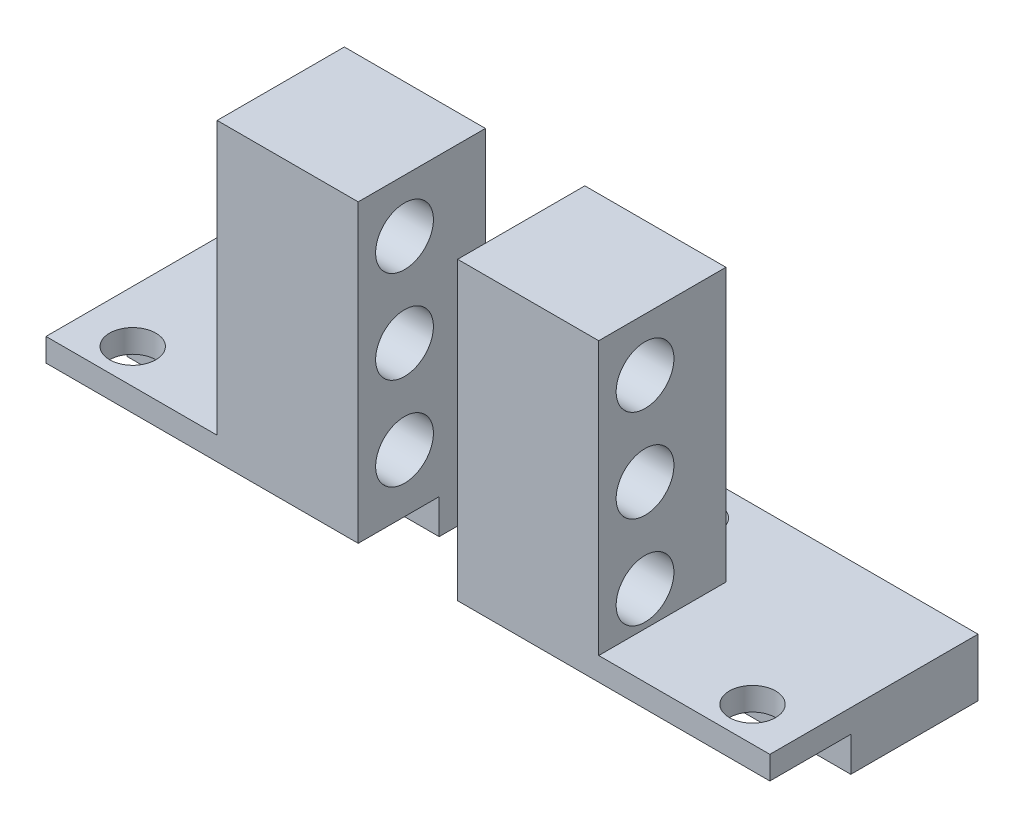
SolidWorks part; units mm, degrees
ref_plane "Front Plane" through (0, 0, 0) normal (0, 0, 1) x (1, 0, 0)
ref_plane "Top Plane" through (0, 0, 0) normal (0, 1, 0) x (1, 0, 0)
ref_plane "Right Plane" through (0, 0, 0) normal (1, 0, 0) x (0, 0, -1)
sketch "Sketch1" plane through (0, 0, 0) normal (0, 0, 1) x (1, 0, 0)
  line L0 (0, 0) -> (12.2, 0)
  line L1 (12.2, 0) -> (12.2, -28.578)
  line L2 (12.2, -28.578) -> (-14.8, -28.578)
  line L3 (-14.8, -28.578) -> (-14.8, -23.578)
  line L4 (-14.8, -23.578) -> (0, -23.578)
  line L5 (0, -23.578) -> (0, 0)
  dimension "D1" = 27
  dimension "D2" = 28.578
  dimension "D3" = 12.2
  dimension "D4" = 5
extrude "Boss-Extrude1" add sketch "Sketch1" against normal blind 18
sketch "Sketch2" plane through (0, 0, 0) normal (-1, 0, 0) x (0, 0, 1)
  line L1 (-18, -23.578) -> (-11, -23.578)
  line L2 (-18, -23.578) -> (-18, 0)
  line L3 (-18, 0) -> (-11, 0)
  line L4 (-11, -23.578) -> (-11, 0)
  line L5 (-18, -23.578) -> (0, -23.578) construction
  line L8 (0, -28.578) -> (-7, -28.578)
  line L9 (0, -28.578) -> (0, -25.578)
  line L10 (0, -25.578) -> (-7, -25.578)
  line L11 (-7, -28.578) -> (-7, -25.578)
  circle A0 centre (-4.0049, -20.578) radius 2.5
  circle A1 centre (-4.0049, -12.578) radius 2.5
  circle A2 centre (-4.0049, -4.578) radius 2.5
  dimension "D2" = 5
  dimension "D1" = 7
  dimension "D3" = 3
  dimension "D4" = 8
  dimension "D5" = 8
  dimension "D6" = 3
  dimension "D7" = 7
extrude "Cut-Extrude1" cut sketch "Sketch2" against normal through all and the other way through all
sketch "Sketch3" plane through (0, -23.578, 0) normal (0, 1, 0) x (1, 0, 0)
  line L0 (12.2, 18) -> (12.2, 11) construction
  line L1 (12.2, 18) -> (12.2, 11) construction
  line L2 (0, 11) -> (0, 0) construction
  line L3 (0, 11) -> (0, 0) construction
  line L4 (12.2, 11) -> (0, 11) construction
  line L5 (12.2, 11) -> (0, 11) construction
  line L6 (-14.8, 18) -> (-14.8, 0) construction
  line L7 (0, 0) -> (-14.8, 0) construction
  circle A0 centre (-10.3, 3) radius 2
  circle A1 centre (6.1, 14.5) radius 2
  point P10 (6.1, 11)
  point P11 (12.2, 14.5)
  dimension "D1" = 4
  dimension "D2" = 4
  dimension "D3" = 4.5
  dimension "D4" = 3
extrude "Cut-Extrude2" cut sketch "Sketch3" against normal through all
ref_plane "Plane1" through (16.5, 0, 0) normal (1, 0, 0) x (0, 0, -1)
mirror "Mirror2" about plane through (16.5, 0, 0) normal (1, 0, 0) of bodies 103
sketch "Sketch4" plane through (12.2, 0, 0) normal (1, 0, 0) x (0, 0, -1)
  line L1 (11, -23.578) -> (18, -23.578)
  line L2 (11, -23.578) -> (11, -28.578)
  line L3 (11, -28.578) -> (18, -28.578)
  line L4 (18, -23.578) -> (18, -28.578)
extrude "Boss-Extrude2" add sketch "Sketch4" along normal up to body
sketch "Sketch5" plane through (0, -23.578, 0) normal (0, 1, 0) x (1, 0, 0)
  line L10 (0, 0) -> (0, 11)
  line L11 (0, 11) -> (12.2, 11)
  line L12 (12.2, 11) -> (20.8, 11)
  line L13 (20.8, 11) -> (33, 11)
  line L14 (33, 11) -> (33, 0)
  line L15 (33, 0) -> (47.8, 0)
  line L16 (47.8, 0) -> (47.8, 18)
  line L17 (47.8, 18) -> (-14.8, 18)
  line L18 (-14.8, 18) -> (-14.8, 0)
  line L19 (-14.8, 0) -> (0, 0)
  line L20 (0, 0) -> (0, 11) construction
  line L21 (0, 11) -> (12.2, 11) construction
  line L22 (12.2, 11) -> (20.8, 11) construction
  line L23 (20.8, 11) -> (33, 11) construction
  line L24 (33, 11) -> (33, 0) construction
  line L25 (33, 0) -> (47.8, 0) construction
  line L26 (47.8, 0) -> (47.8, 18) construction
  line L27 (47.8, 18) -> (-14.8, 18) construction
  line L28 (-14.8, 18) -> (-14.8, 0) construction
  line L29 (-14.8, 0) -> (0, 0) construction
  circle A0 centre (-10.3, 3) radius 2 construction
  circle A1 centre (43.3, 3) radius 2 construction
  circle A2 centre (26.9, 14.5) radius 2 construction
  circle A3 centre (6.1, 14.5) radius 2 construction
  circle A4 centre (-10.3, 3) radius 2 construction
  circle A5 centre (43.3, 3) radius 2 construction
  circle A6 centre (26.9, 14.5) radius 2 construction
  circle A7 centre (6.1, 14.5) radius 2 construction
  dimension "D1" = 0
